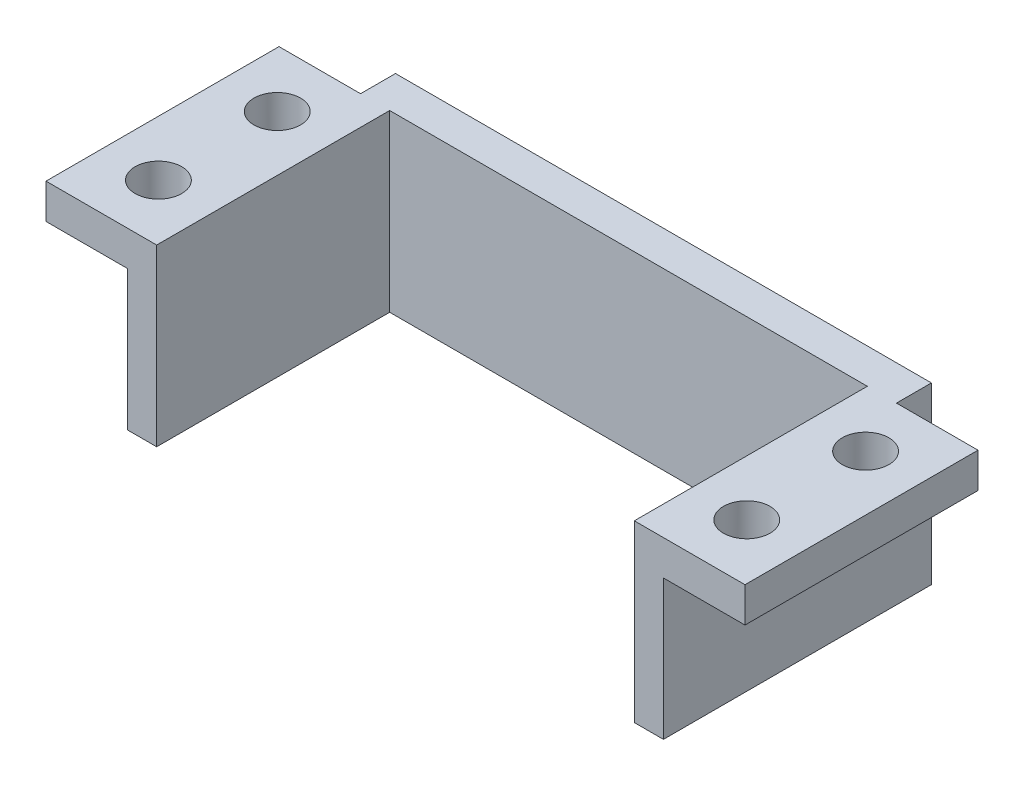
SolidWorks part; units mm, degrees
ref_plane "Front Plane" through (0, 0, 0) normal (0, 0, 1) x (1, 0, 0)
ref_plane "Top Plane" through (0, 0, 0) normal (0, 1, 0) x (1, 0, 0)
ref_plane "Right Plane" through (0, 0, 0) normal (1, 0, 0) x (0, 0, -1)
sketch "Sketch1" plane through (0, 0, 0) normal (0, 0, 1) x (1, 0, 0)
  line L1 (0, 0) -> (46, 0)
  line L2 (0, 0) -> (0, 15)
  line L3 (0, 15) -> (46, 15)
  line L4 (46, 0) -> (46, 15)
  dimension "D1" = 46
  dimension "D2" = 15
extrude "Boss-Extrude1" add sketch "Sketch1" along normal blind 3
sketch "Sketch3" plane through (0, 0, 3) normal (0, 0, 1) x (1, 0, 0)
  line L1 (0, 0) -> (2.5, 0)
  line L2 (0, 0) -> (0, 15)
  line L3 (0, 15) -> (2.5, 15)
  line L4 (2.5, 0) -> (2.5, 15)
  dimension "D1" = 15
  dimension "D2" = 2.5
extrude "Boss-Extrude2" add sketch "Sketch3" along normal blind 20
sketch "Sketch4" plane through (0, 0, 0) normal (-1, 0, 0) x (0, 0, 1)
  line L1 (23, 15) -> (3, 15)
  line L2 (23, 15) -> (23, 12)
  line L3 (23, 12) -> (3, 12)
  line L4 (3, 15) -> (3, 12)
  dimension "D1" = 3
  dimension "D2" = 20
extrude "Boss-Extrude3" add sketch "Sketch4" along normal blind 7
sketch "Sketch5" plane through (0, 15, 0) normal (0, 1, 0) x (1, 0, 0)
  line L0 (0, -3) -> (0, -23) construction
  line L1 (-2.25, -23) -> (-2.25, -20.35) construction
  line L2 (2.5, -23) -> (-7, -23) construction
  line L3 (-2.25, -23) -> (0, -23) construction
  line L4 (-7, -13) -> (2.5, -13) construction
  line L5 (-7, -23) -> (-7, -3) construction
  line L6 (2.5, -23) -> (2.5, -3) construction
  circle A0 centre (-2.25, -18.1) radius 2.25 construction
  circle A1 centre (-2.25, -18.1) radius 2
  circle A2 centre (-2.25, -7.9) radius 2
  dimension "D2" = 4.5
  dimension "D4" = 4
  dimension "D1" = 2.65
  dimension "D3" = 2.25
extrude "Cut-Extrude1" cut sketch "Sketch5" against normal blind 7
ref_plane "Plane1" through (23, 0, 0) normal (1, 0, 0) x (0, 0, -1)
mirror "Mirror1" about plane through (23, 0, 0) normal (1, 0, 0) of "Boss-Extrude2", "Boss-Extrude3", "Cut-Extrude1"
